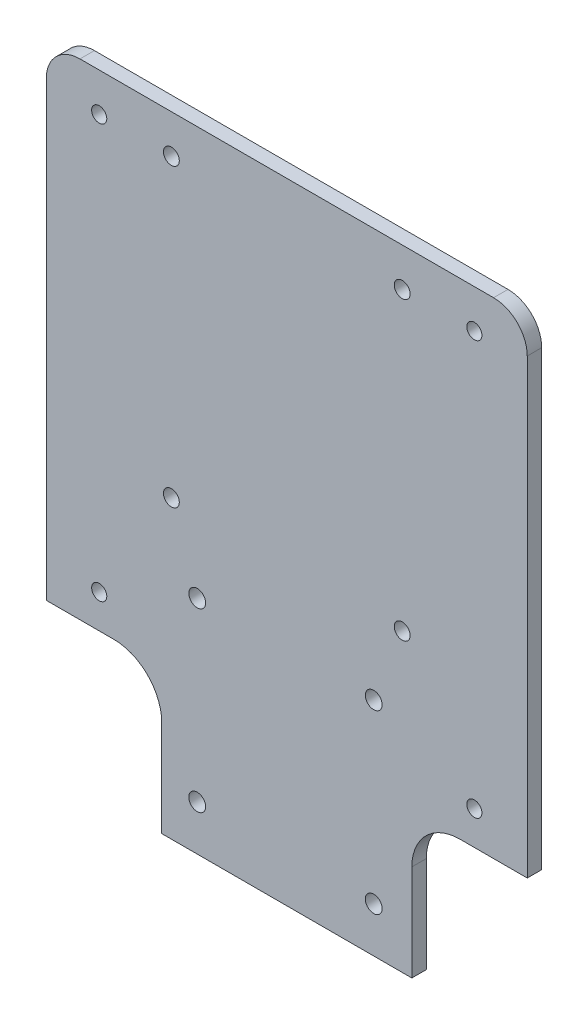
SolidWorks part; units mm, degrees
ref_plane "Front Plane" through (0, 0, 0) normal (0, 0, 1) x (1, 0, 0)
ref_plane "Top Plane" through (0, 0, 0) normal (0, 1, 0) x (1, 0, 0)
ref_plane "Right Plane" through (0, 0, 0) normal (1, 0, 0) x (0, 0, -1)
ref_plane "Plane1" through (0, 0, 27) normal (0, 0, 1) x (1, 0, 0)
sketch "Sketch2" plane through (0, 0, 27) normal (0, 0, 1) x (1, 0, 0)
  line L0 (50, 113.9439) -> (50, 149) construction
  line L1 (-50, 113.9439) -> (-50, 149) construction
  line L2 (-43, 156) -> (43, 156) construction
  line L3 (50, 113.9439) -> (50, 149)
  line L4 (-50, 113.9439) -> (-50, 149)
  line L5 (-43, 156) -> (43, 156)
  line L6 (-50, 113.9439) -> (-50, 55)
  line L12 (50, 55) -> (50, 113.9439)
  line L13 (-50, 55) -> (-26, 55)
  line L18 (-26, 55) -> (-26, 25)
  line L19 (-26, 25) -> (26, 25)
  line L20 (26, 25) -> (26, 55)
  line L21 (26, 55) -> (50, 55)
  arc A0 (50, 149) -> (43, 156) centre (43, 149) ccw construction
  arc A1 (-43, 156) -> (-50, 149) centre (-43, 149) ccw construction
  arc A2 (50, 149) -> (43, 156) centre (43, 149) ccw
  arc A3 (-43, 156) -> (-50, 149) centre (-43, 149) ccw
  circle A6 centre (39, 62) radius 1.575 construction
  circle A7 centre (-39, 62) radius 1.575 construction
  circle A8 centre (39, 148) radius 1.575 construction
  circle A9 centre (-39, 148) radius 1.575 construction
  circle A10 centre (39, 62) radius 1.575
  circle A11 centre (-39, 62) radius 1.575
  circle A12 centre (39, 148) radius 1.575
  circle A13 centre (-39, 148) radius 1.575
  circle A14 centre (-18.6214, 71.0948) radius 1.75
  circle A15 centre (18.0786, 71.0948) radius 1.75
  circle A16 centre (-18.6214, 34.3948) radius 1.75
  circle A17 centre (18.0786, 34.3948) radius 1.75
  dimension "D2" = 52
  dimension "D3" = 3.5
  dimension "D1" = 30
extrude "Boss-Extrude1" add sketch "Sketch2" along normal blind 3
sketch "Sketch3" plane through (0, 0, 30) normal (0, 0, 1) x (1, 0, 0)
  line L0 (0, 156) -> (0, 79.9573) construction
  line L1 (43, 156) -> (-43, 156) construction
  line L2 (-25, 79.9573) -> (25, 79.9573) construction
  circle A0 centre (-24, 147.9787) radius 1.65
  circle A1 centre (24, 86.4787) radius 1.65
  circle A2 centre (-24, 86.4787) radius 1.65
  circle A3 centre (24, 147.9787) radius 1.65
  dimension "D1" = 3.3
  dimension "D2" = 3.3
extrude "Cut-Extrude1" cut sketch "Sketch3" against normal blind 10
fillet "Fillet1" radius 10 2 edges at (26, 55, 28.5) (-26, 55, 28.5)
